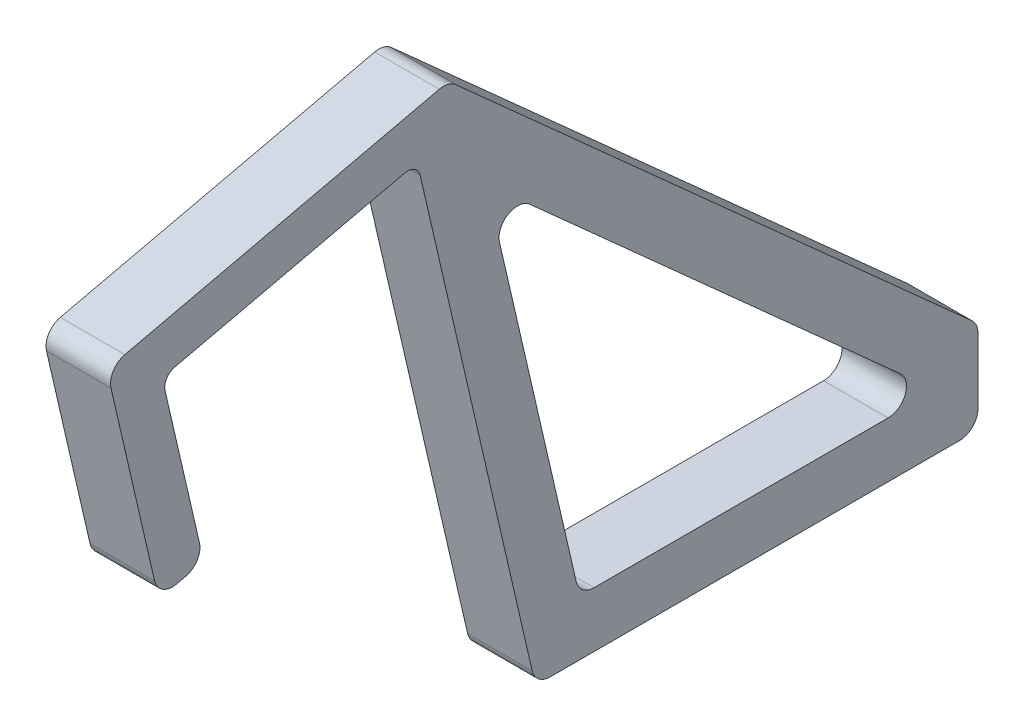
SolidWorks part; units mm, degrees
material "PLA2"
ref_plane "Front Plane" through (0, 0, 0) normal (0, 0, 1) x (1, 0, 0)
ref_plane "Top Plane" through (0, 0, 0) normal (0, 1, 0) x (1, 0, 0)
ref_plane "Right Plane" through (0, 0, 0) normal (1, 0, 0) x (0, 0, -1)
sketch "Sketch1" plane through (0, 0, 0) normal (1, 0, 0) x (0, 0, -1)
  line L0 (0, 0) -> (30.48, 0)
  line L1 (30.48, 0) -> (30.48, 6.35)
  line L2 (-8.1421, 35.2673) -> (-1.7921, 35.2673)
  line L5 (0, 0) -> (-8.1421, 35.2673)
  line L7 (-1.7921, 35.2673) -> (30.48, 6.35)
  line L8 (0, 0) -> (0, 50000) construction
  dimension "D1" = 30.48
  dimension "D2" = 6.35
  dimension "D3" = 6.35
  dimension "D4" = 36.195
  dimension "D5" = 13
extrude "Boss-Extrude1" add sketch "Sketch1" along normal blind 4.445
sketch "Sketch2" plane through (4.445, 0, 0) normal (1, 0, 0) x (0, 0, -1)
  line L0 (-8.1421, 35.2673) -> (-25.7139, 31.2106)
  line L1 (-8.1421, 35.2673) -> (0, 0) construction
  line L2 (-25.7139, 31.2106) -> (-22.857, 18.8361)
  line L3 (-22.857, 18.8361) -> (-25.9506, 18.1218)
  line L4 (-25.9506, 18.1218) -> (-29.5217, 33.59)
  line L5 (-29.5217, 33.59) -> (-5.9845, 39.024)
  line L6 (-5.9845, 39.024) -> (-1.7921, 35.2673)
  line L7 (30.48, 6.35) -> (-1.7921, 35.2673) construction
  line L8 (-8.1421, 35.2673) -> (-1.7921, 35.2673)
  dimension "D1" = 18.034
  dimension "D2" = 3.175
  dimension "D3" = 3.175
  dimension "D4" = 12.7
extrude "Boss-Extrude2" add sketch "Sketch2" against normal up to surface (4.445 mm away) up to face at (0, 15.3769, -10.2052)
fillet "Fillet1" radius 0.889 2 edges at (2.2225, 35.2673, 8.1421) (2.2225, 31.2106, 25.7139)
fillet "Fillet2" radius 1.27 7 edges at (2.2225, 18.8361, 22.857) (2.2225, 18.1218, 25.9506) (2.2225, 33.59, 29.5217) (2.2225, 39.024, 5.9845) (2.2225, 6.35, -30.48) (2.2225, 0, -30.48) (2.2225, 0, 0)
sketch "Sketch3" plane through (4.445, 0, 0) normal (1, 0, 0) x (0, 0, -1)
  line L0 (-3.3791, 31.5736) -> (3.0306, 3.81)
  line L1 (3.0306, 3.81) -> (27.6054, 3.81)
  line L2 (27.6054, 3.81) -> (-3.3791, 31.5736)
  line L3 (30.0575, 6.7286) -> (-5.4936, 38.5841) construction
  line L4 (1.0102, 0) -> (29.21, 0) construction
  line L5 (-7.9421, 34.4011) -> (-0.2272, 0.9843) construction
  dimension "D1" = 3.81
  dimension "D2" = 3.81
  dimension "D3" = 3.81
extrude "Cut-Extrude1" cut sketch "Sketch3" against normal through all
fillet "Fillet3" radius 1.27 3 edges at (2.2225, 3.81, -27.6054) (2.2225, 31.5736, 3.3791) (2.2225, 3.81, -3.0306)
